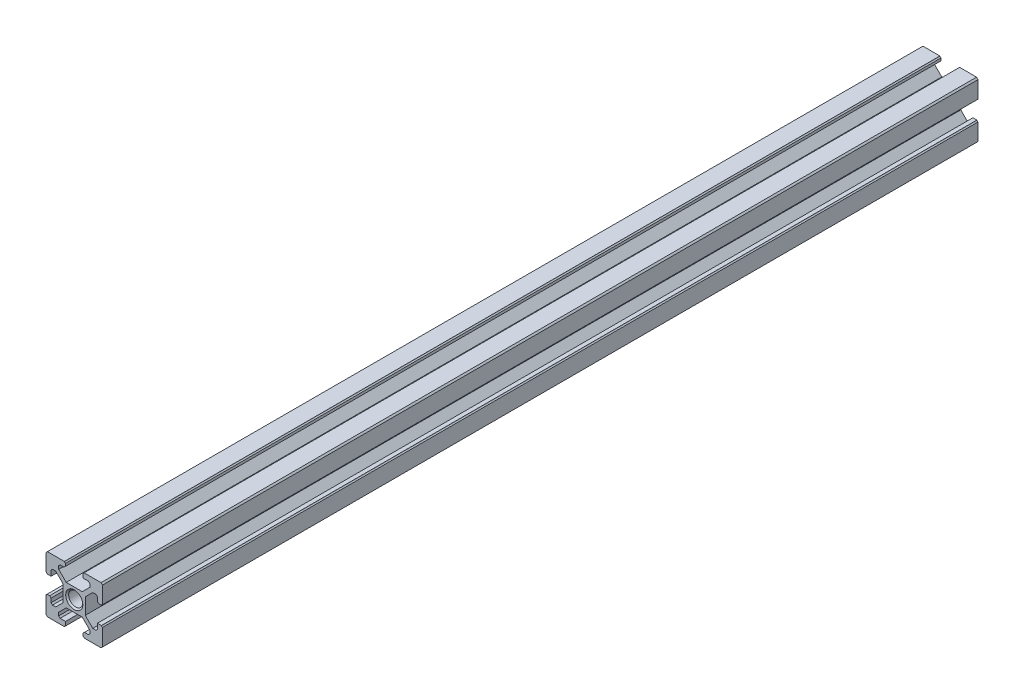
SolidWorks part; units mm, degrees
ref_plane "Front Plane" through (0, 0, 0) normal (0, 0, 1) x (1, 0, 0)
ref_plane "Top Plane" through (0, 0, 0) normal (0, 1, 0) x (1, 0, 0)
ref_plane "Right Plane" through (0, 0, 0) normal (1, 0, 0) x (0, 0, -1)
sketch "Sketch1" plane through (0, 0, 0) normal (0, 0, 1) x (1, 0, 0)
  line L0 (0, 10.7337) -> (0, 0.7337) construction
  line L1 (-9.5, 10) -> (-3.4865, 10)
  line L2 (-10, 9.5) -> (-10, 3.4865)
  line L3 (-9.5, -10) -> (-3.4865, -10)
  line L4 (10, 9.5) -> (10, 3.4865)
  line L5 (-9.75, 9.75) -> (9.75, -9.75) construction
  line L6 (-9.75, -9.75) -> (10, 10) construction
  line L7 (0, 0) -> (-10, 0) construction
  line L8 (3.1, 9.6135) -> (3.1, 8.2)
  line L9 (3.1, 8.2) -> (5, 8.2)
  line L10 (5.5, 7.7) -> (5.5, 6.5607)
  line L11 (5.5, 6.5607) -> (2.8393, 3.9)
  line L12 (2.8393, 3.9) -> (0, 3.9)
  line L13 (3.9, 2.8393) -> (3.9, 0)
  line L14 (6.5607, 5.5) -> (3.9, 2.8393)
  line L15 (9.6135, 3.1) -> (8.7, 3.1)
  line L16 (8.2, 3.6) -> (8.2, 5)
  line L17 (7.7, 5.5) -> (6.5607, 5.5)
  line L18 (3.4865, 10) -> (9.5, 10)
  line L19 (10, -3.4865) -> (10, -9.5)
  line L20 (5, 8.2) -> (5.5, 7.7)
  line L21 (8.2, 5) -> (7.7, 5.5)
  line L22 (9.5, 10) -> (10, 9.5)
  line L23 (8.7, 3.1) -> (8.2, 3.6)
  line L24 (3.9, -2.8393) -> (3.9, 0)
  line L25 (6.5607, -5.5) -> (3.9, -2.8393)
  line L26 (7.7, -5.5) -> (6.5607, -5.5)
  line L27 (8.2, -5) -> (7.7, -5.5)
  line L28 (8.2, -3.1) -> (8.2, -5)
  line L29 (9.6135, -3.1) -> (8.2, -3.1)
  line L30 (10, -3.4865) -> (10, -9.5)
  line L31 (10, -9.5) -> (9.5, -10)
  line L32 (9.5, -10) -> (3.4865, -10)
  line L33 (3.1, -9.6135) -> (3.1, -8.7)
  line L34 (3.1, -8.7) -> (3.6, -8.2)
  line L35 (3.6, -8.2) -> (5, -8.2)
  line L36 (5, -8.2) -> (5.5, -7.7)
  line L37 (5.5, -7.7) -> (5.5, -6.5607)
  line L38 (5.5, -6.5607) -> (2.8393, -3.9)
  line L39 (2.8393, -3.9) -> (0, -3.9)
  line L40 (-2.8393, -3.9) -> (0, -3.9)
  line L41 (-5.5, -6.5607) -> (-2.8393, -3.9)
  line L42 (-5.5, -7.7) -> (-5.5, -6.5607)
  line L43 (-5, -8.2) -> (-5.5, -7.7)
  line L44 (-3.1, -8.2) -> (-5, -8.2)
  line L45 (-3.1, -9.6135) -> (-3.1, -8.2)
  line L46 (-3.4865, -10) -> (-9.5, -10)
  line L47 (-9.5, -10) -> (-10, -9.5)
  line L48 (-10, -9.5) -> (-10, -3.4865)
  line L49 (-9.6135, -3.1) -> (-8.7, -3.1)
  line L50 (-8.7, -3.1) -> (-8.2, -3.6)
  line L51 (-8.2, -3.6) -> (-8.2, -5)
  line L52 (-8.2, -5) -> (-7.7, -5.5)
  line L53 (-7.7, -5.5) -> (-6.5607, -5.5)
  line L54 (-6.5607, -5.5) -> (-3.9, -2.8393)
  line L55 (-3.9, -2.8393) -> (-3.9, 0)
  line L56 (-3.9, 2.8393) -> (-3.9, 0)
  line L57 (-6.5607, 5.5) -> (-3.9, 2.8393)
  line L58 (-7.7, 5.5) -> (-6.5607, 5.5)
  line L59 (-8.2, 5) -> (-7.7, 5.5)
  line L60 (-8.2, 3.1) -> (-8.2, 5)
  line L61 (-9.6135, 3.1) -> (-8.2, 3.1)
  line L62 (-10, 3.4865) -> (-10, 9.5)
  line L63 (-10, 9.5) -> (-9.5, 10)
  line L64 (-9.5, 10) -> (-3.4865, 10)
  line L65 (-3.1, 9.6135) -> (-3.1, 8.7)
  line L66 (-3.1, 8.7) -> (-3.6, 8.2)
  line L67 (-3.6, 8.2) -> (-5, 8.2)
  line L68 (-5, 8.2) -> (-5.5, 7.7)
  line L69 (-5.5, 7.7) -> (-5.5, 6.5607)
  line L70 (-5.5, 6.5607) -> (-2.8393, 3.9)
  line L71 (-2.8393, 3.9) -> (0, 3.9)
  line L72 (3.4865, -10) -> (9.5, -10)
  line L73 (-10, -3.4865) -> (-10, -9.5)
  arc A0 (3.1, 9.6135) -> (3.4865, 10) centre (3.1, 10) ccw
  arc A1 (9.6135, 3.1) -> (10, 3.4865) centre (10, 3.1) cw
  arc A2 (9.6135, -3.1) -> (10, -3.4865) centre (10, -3.1) ccw
  arc A3 (3.1, -9.6135) -> (3.4865, -10) centre (3.1, -10) cw
  arc A4 (-3.1, -9.6135) -> (-3.4865, -10) centre (-3.1, -10) ccw
  arc A5 (-9.6135, -3.1) -> (-10, -3.4865) centre (-10, -3.1) cw
  arc A6 (-9.6135, 3.1) -> (-10, 3.4865) centre (-10, 3.1) ccw
  arc A7 (-3.1, 9.6135) -> (-3.4865, 10) centre (-3.1, 10) cw
  point P0 (0, 0)
  point P13 (5.5, 8.2)
  point P17 (3.1, 8.9068)
  point P22 (8.2, 3.1)
  point P23 (8.2, 5.5)
  point P103 (0, 0)
  dimension "D3" = 1.8
  dimension "D4" = 6.1
  dimension "D5" = 11
  dimension "D6" = 6.2
  dimension "D7" = 1.5
extrude "Boss-Extrude1" add sketch "Sketch1" along normal blind 310 contours L65 A7 L1 L63 L2 A6 L61 L60 L59 L58 L57 L56 L55 L54 L53 L52 L51 L50 L49 A5 L48 L47 L3 A4 L45 L44 L43 L42 L41 L40 L39 L38 L37 L36 L35 L34 L33 A3 L32 L31 L19 A2 L29 L28 L27 L26 L25 L24 L13 L14 L17
hole_wizard "M6x1.0 Tapped Hole1" positions "3DSketch1" profile "Sketch2" tap size "M6x1.0" standard "ANSI Metric"
sketch3d "3DSketch1"
  line L0 (3.9, -2.8393, 310) -> (3.9, 2.8393, 310) construction
  line L1 (2.8393, 3.9, 310) -> (-2.8393, 3.9, 310) construction
  point P0 (0, 0, 0)
  point P3 (0, 0, 0)
  point P5 (0, 0, 0)
  point P7 (0.9996, -8.1302, 0)
  point P9 (0, 0, 0)
  point P11 (0, 0, 310)
  dimension "D1" = 3.9
  dimension "D2" = 3.9
sketch "Sketch2" plane through (0, 0, 310) normal (1, 0, 0) x (0, -1, 0)
  line L0 (0, 0) -> (0, 30)
  line L1 (0, 30) -> (2.5, 28.4978)
  line L2 (2.5, 28.4978) -> (2.5, 0.525)
  line L3 (2.5, 0.525) -> (3.025, 0)
  line L5 (3.025, 0) -> (0, 0)
  line L6 (-2.5, 0.525) -> (-3.025, 0) construction
  line L10 (0, 30) -> (-2.5, 28.4978) construction
  line L11 (0, -6.35) -> (0, 107.95) construction
  dimension "Tap Drill Dia." = 5
  dimension "Tap Drill Depth" = 30
  dimension "Near C'Sink Dia." = 6.05
  dimension "Near C'Sink Angle" = 90
  dimension "Drill Angle" = 118
cosmetic thread "Hole Thread6"
hole_wizard "M6x1.0 Tapped Hole2" positions "3DSketch2" profile "Sketch3" tap size "M6x1.0" standard "ANSI Metric"
sketch3d "3DSketch2"
  line L0 (2.8393, 3.9, 0) -> (-2.8393, 3.9, 0) construction
  line L1 (3.9, -2.8393, 0) -> (3.9, 2.8393, 0) construction
  point P3 (0, 0, 0)
  dimension "D1" = 3.9
  dimension "D2" = 3.9
sketch "Sketch3" plane through (0, 0, 0) normal (1, 0, 0) x (0, 1, 0)
  line L0 (0, 0) -> (0, 30)
  line L1 (0, 30) -> (2.5, 28.4978)
  line L2 (2.5, 28.4978) -> (2.5, 0.525)
  line L3 (2.5, 0.525) -> (3.025, 0)
  line L5 (3.025, 0) -> (0, 0)
  line L6 (-2.5, 0.525) -> (-3.025, 0) construction
  line L10 (0, 30) -> (-2.5, 28.4978) construction
  line L11 (0, -6.35) -> (0, 107.95) construction
  dimension "Tap Drill Dia." = 5
  dimension "Tap Drill Depth" = 30
  dimension "Near C'Sink Dia." = 6.05
  dimension "Near C'Sink Angle" = 90
  dimension "Drill Angle" = 118
cosmetic thread "Hole Thread7"
